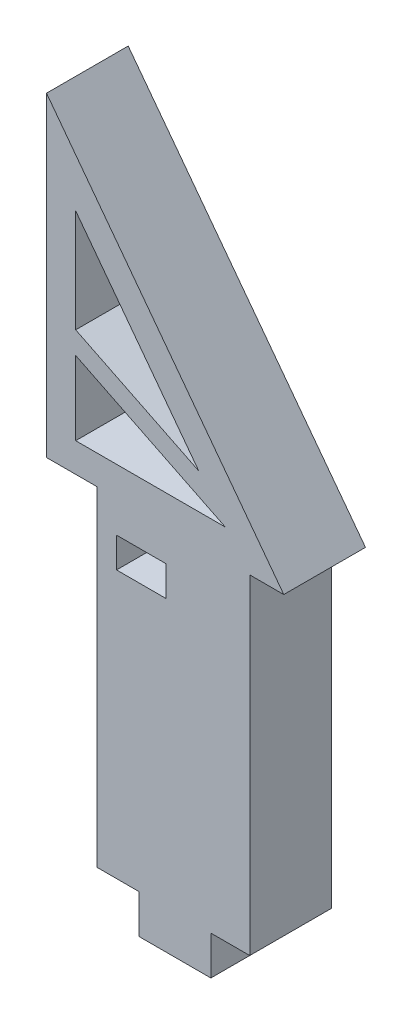
SolidWorks part; units mm, degrees
material "ABS"
ref_plane "正面" through (0, 0, 0) normal (0, 0, 1) x (1, 0, 0)
ref_plane "平面" through (0, 0, 0) normal (0, 1, 0) x (1, 0, 0)
ref_plane "右側面" through (0, 0, 0) normal (1, 0, 0) x (0, 0, -1)
sketch "ｽｹｯﾁ1" plane through (0, 0, 0) normal (0, 1, 0) x (1, 0, 0)
  line L1 (7.85, -4.2) -> (-7.85, -4.2)
  line L2 (7.85, -4.2) -> (7.85, 4.2)
  line L3 (7.85, 4.2) -> (-7.85, 4.2)
  line L4 (-7.85, -4.2) -> (-7.85, 4.2)
  line L5 (7.85, -4.2) -> (-7.85, 4.2) construction
  line L6 (7.85, 4.2) -> (-7.85, -4.2) construction
  point P0 (0, 0)
  dimension "D1" = 8.4
  dimension "D2" = 15.7
extrude "ﾎﾞｽ - 押し出し1" add sketch "ｽｹｯﾁ1" along normal blind 37.9
sketch "ｽｹｯﾁ2" plane through (0, 0, 4.2) normal (0, 0, 1) x (1, 0, 0)
  line L0 (-13.05, 37.9) -> (11.35, 37.9)
  line L1 (11.35, 37.9) -> (-13.05, 70.35)
  line L2 (-13.05, 70.35) -> (-13.05, 37.9)
  line L3 (7.85, 37.9) -> (7.85, 0) construction
  line L4 (-7.85, 37.9) -> (-7.85, 0) construction
  dimension "D1" = 3.5
  dimension "D2" = 5.2
  dimension "D3" = 32.45
extrude "ﾎﾞｽ - 押し出し2" add sketch "ｽｹｯﾁ2" against normal blind 8.4
sketch "ｽｹｯﾁ3" plane through (0, 0, -4.2) normal (0, 0, -1) x (-1, 0, 0)
  line L0 (10.05, 61.3684) -> (-2.6109, 44.5305)
  line L1 (-5.3408, 40.9) -> (10.05, 40.9)
  line L2 (10.05, 40.9) -> (10.05, 48.4875)
  line L3 (13.05, 37.9) -> (7.85, 37.9) construction
  line L4 (13.05, 70.35) -> (13.05, 37.9) construction
  line L5 (-11.35, 37.9) -> (13.05, 70.35) construction
  line L6 (-2.6109, 44.5305) -> (10.05, 50.7722)
  line L8 (10.05, 48.4875) -> (-5.3408, 40.9)
  line L9 (10.05, 50.7722) -> (10.05, 61.3684)
  point P5 (10.45, 37.9)
  dimension "D1" = 3
  dimension "D2" = 3
  dimension "D3" = 3
extrude "ｶｯﾄ - 押し出し1" cut sketch "ｽｹｯﾁ3" against normal through all
sketch "ｽｹｯﾁ4" plane through (0, 0, -4.2) normal (0, 0, -1) x (-1, 0, 0)
  line L1 (3.55, 4) -> (7.85, 4)
  line L2 (3.55, 4) -> (3.55, 0)
  line L3 (3.55, 0) -> (7.85, 0)
  line L4 (7.85, 4) -> (7.85, 0)
  line L5 (3.55, 4) -> (7.85, 0) construction
  line L6 (3.55, 0) -> (7.85, 4) construction
  line L7 (-3.85, 4) -> (-7.85, 4)
  line L8 (-3.85, 4) -> (-3.85, 0)
  line L9 (-3.85, 0) -> (-7.85, 0)
  line L10 (-7.85, 4) -> (-7.85, 0)
  line L11 (-3.85, 4) -> (-7.85, 0) construction
  line L12 (-3.85, 0) -> (-7.85, 4) construction
  point P0 (5.7, 2)
  point P6 (-5.85, 2)
  dimension "D1" = 4.3
  dimension "D2" = 4
extrude "ｶｯﾄ - 押し出し2" cut sketch "ｽｹｯﾁ4" against normal through all
sketch "ｽｹｯﾁ5" plane through (0, 0, -4.2) normal (0, 0, -1) x (-1, 0, 0)
  line L0 (-5.3408, 40.9) -> (10.05, 40.9) construction
  line L1 (0.75, 31.49) -> (5.85, 31.49)
  line L2 (0.75, 31.49) -> (0.75, 34.59)
  line L3 (0.75, 34.59) -> (5.85, 34.59)
  line L4 (5.85, 31.49) -> (5.85, 34.59)
  line L5 (0.75, 31.49) -> (5.85, 34.59) construction
  line L6 (0.75, 34.59) -> (5.85, 31.49) construction
  line L7 (7.85, 37.9) -> (7.85, 4) construction
  point P0 (3.3, 33.04)
  dimension "D1" = 9.41
  dimension "D2" = 3.1
  dimension "D3" = 2
  dimension "D4" = 5.1
extrude "ｶｯﾄ - 押し出し3" cut sketch "ｽｹｯﾁ5" against normal through all
